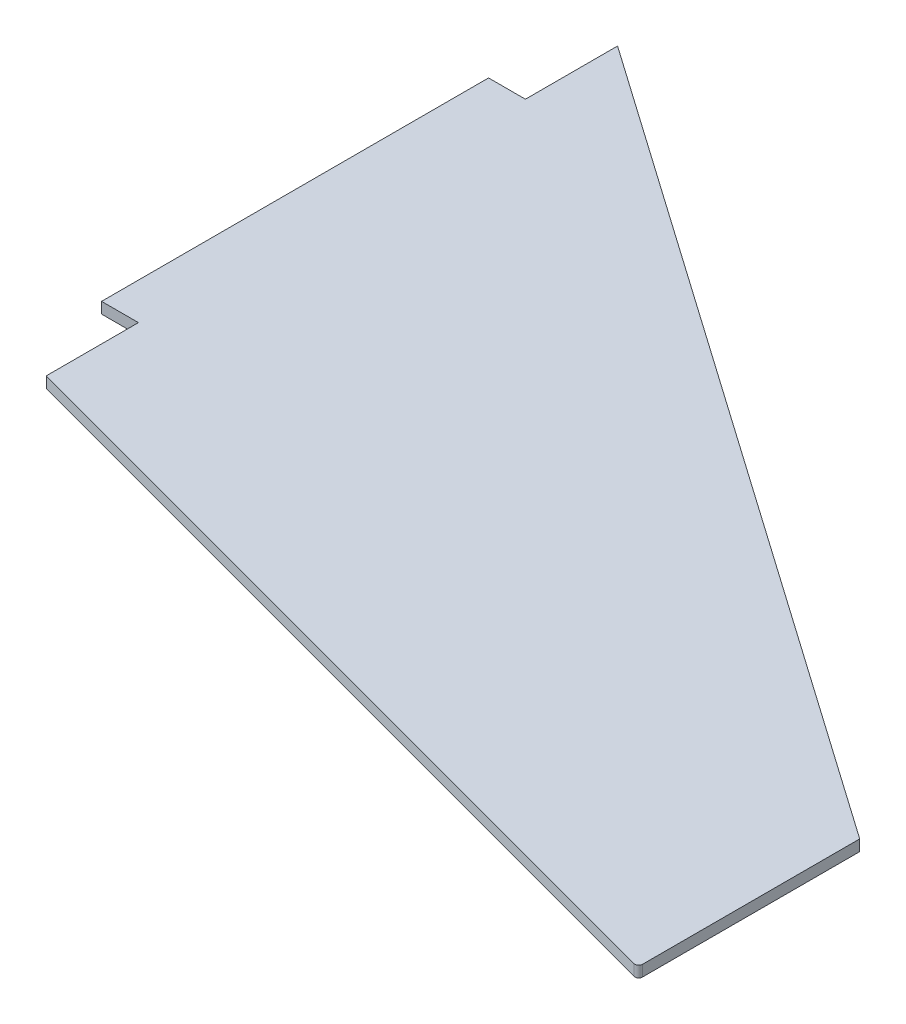
SolidWorks part; units mm, degrees
ref_plane "Front Plane" through (0, 0, 0) normal (0, 0, 1) x (1, 0, 0)
ref_plane "Top Plane" through (0, 0, 0) normal (0, 1, 0) x (1, 0, 0)
ref_plane "Right Plane" through (0, 0, 0) normal (1, 0, 0) x (0, 0, -1)
sketch "Sketch1" plane through (0, 0, 0) normal (0, 1, 0) x (1, 0, 0)
  line L0 (0, -130) -> (0, -105)
  line L1 (0, 0) -> (-10, 0)
  line L3 (0, -105) -> (-10, -105)
  line L4 (-10, 0) -> (-10, -105)
  line L5 (219.162, -187.4211) -> (219.162, -128.4589)
  line L6 (219.162, -128.4589) -> (0, 25)
  line L7 (217.9032, -188.387) -> (0, -130)
  line L8 (0, 0) -> (0, 25)
  line L9 (0, 25) -> (10.3201, 25) construction
  arc A0 (219.162, -187.4211) -> (217.9032, -188.387) centre (218.162, -187.4211) cw
  point P14 (219.162, -188.7243)
  dimension "D7" = 1
  dimension "D1" = 10
  dimension "D2" = 105
  dimension "D5" = 155
  dimension "D3" = 35
  dimension "D4" = 105
  dimension "D6" = 125
  dimension "D8" = 75
  dimension "D9" = 219.162
  dimension "D10" = 25
extrude "Boss-Extrude1" add sketch "Sketch1" along normal blind 3
equation "\"largo de contacto del brazo\" =10"
equation "\"D1@Sketch1\"=\"largo de contacto del brazo\""
equation "\"alto brazo de contacto\" =105"
equation "\"D2@Sketch1\"=\"alto brazo de contacto\""
equation "\"Tip chord\"=16.3499"
equation "\"Root chor\"=34.0006"
equation "\"Semi span\"=43.8324"
equation "\"fins Thicknes\"= 3"
equation "\"D1@Boss-Extrude1\"=\"fins Thicknes\""
equation "\"Redonde de impacto\"= 1"
equation "\"D7@Sketch1\"=\"Redonde de impacto\""
equation "\"sweep angle\"= 35"
equation "\"D3@Sketch1\"=\"sweep angle\""
